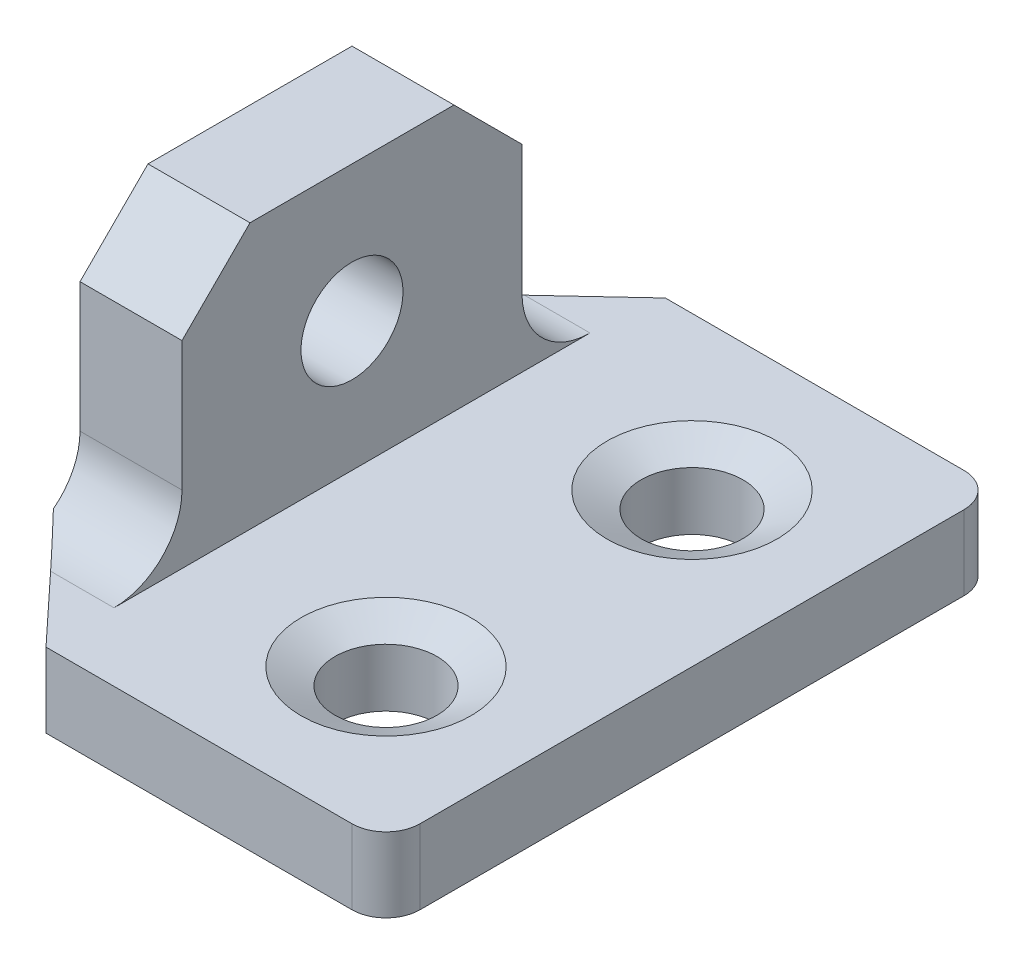
SolidWorks part; units mm, degrees
ref_plane "Front Plane" through (0, 0, 0) normal (0, 0, 1) x (1, 0, 0)
ref_plane "Top Plane" through (0, 0, 0) normal (0, 1, 0) x (1, 0, 0)
ref_plane "Right Plane" through (0, 0, 0) normal (1, 0, 0) x (0, 0, -1)
sketch "Sketch1" plane through (0, 0, 0) normal (0, 1, 0) x (1, 0, 0)
  line L1 (-35, -75) -> (35, -75)
  line L2 (-35, -75) -> (-35, 75)
  line L3 (-35, 75) -> (35, 75)
  line L4 (35, -75) -> (35, 75)
  line L5 (-35, -75) -> (35, 75) construction
  line L6 (-35, 75) -> (35, -75) construction
  point P0 (0, 0)
  dimension "D1" = 150
  dimension "D2" = 70
extrude "Boss-Extrude1" add sketch "Sketch1" along normal blind 5
sketch "Sketch2" plane through (0, 5, 0) normal (0, 1, 0) x (1, 0, 0)
  line L1 (-9, 55) -> (-5, 55)
  line L2 (-9, 55) -> (-9, 70)
  line L3 (-9, 70) -> (-5, 70)
  line L4 (-5, 55) -> (-5, 70)
  line L5 (-9, 55) -> (-5, 70) construction
  line L6 (-9, 70) -> (-5, 55) construction
  line L7 (5, 55) -> (9, 55)
  line L8 (5, 55) -> (5, 70)
  line L9 (5, 70) -> (9, 70)
  line L10 (9, 55) -> (9, 70)
  line L11 (5, 55) -> (9, 70) construction
  line L12 (5, 70) -> (9, 55) construction
  line L13 (0, 0) -> (0, 57.2395) construction
  line L14 (35, 75) -> (-35, 75) construction
  point P0 (-7, 62.5)
  point P5 (7, 62.5)
  dimension "D1" = 15
  dimension "D2" = 15
  dimension "D3" = 4
  dimension "D4" = 4
  dimension "D5" = 10
  dimension "D6" = 5
  dimension "D7" = 5
  dimension "D8" = 5
extrude "Boss-Extrude2" add sketch "Sketch2" along normal blind 15
sketch "Sketch3" plane through (-5, 0, 0) normal (1, 0, 0) x (0, 0, -1)
  line L0 (55, 20) -> (70, 20) construction
  line L1 (55, 20) -> (55, 5) construction
  circle A0 centre (62.5, 12.5) radius 3
  dimension "D1" = 6
  dimension "D2" = 7.5
  dimension "D3" = 7.5
extrude "Boss-Extrude3" add sketch "Sketch3" along normal up to next contours A0
chamfer "Chamfer1" distance 4 angle 45 4 edges at (-7, 20, -55) (7, 20, -55) (7, 20, -70) (-7, 20, -70)
chamfer "Chamfer2" distance 4 angle 45 4 edges at (-7, 5, -70) (7, 5, -70) (7, 5, -55) (-7, 5, -55)
chamfer "Chamfer3" distance 4 angle 45 2 edges at (9, 5, -62.5) (-9, 5, -62.5)
chamfer "Chamfer4" distance 10 angle 45 2 edges at (35, 2.5, -75) (-35, 2.5, -75)
chamfer "Chamfer5" distance 20 angle 45 2 edges at (-35, 2.5, 75) (35, 2.5, 75)
sketch "Sketch4" plane through (0, 5, 0) normal (0, 1, 0) x (1, 0, 0)
  line L0 (0, 0) -> (0, -85.4212) construction
  line L1 (25, -20) -> (25, -30)
  line L2 (25, -30) -> (28, -30)
  line L3 (28, -30) -> (28, -20)
  line L4 (28, -20) -> (25, -20)
  line L5 (-15, -75) -> (15, -75) construction
  line L6 (-25, -30) -> (-28, -30)
  line L7 (-28, -20) -> (-25, -20)
  line L8 (-28, -30) -> (-28, -20)
  line L9 (-25, -20) -> (-25, -30)
  dimension "D1" = 0
  dimension "D2" = 3
  dimension "D3" = 10
  dimension "D4" = 45
  dimension "D5" = 25
extrude "Boss-Extrude4" add sketch "Sketch4" along normal blind 10
chamfer "Chamfer6" distance 2 angle 45 4 edges at (-26.5, 15, 30) (-26.5, 15, 20) (26.5, 15, 20) (26.5, 15, 30)
sketch "Sketch5" plane through (28, 0, 0) normal (1, 0, 0) x (0, 0, -1)
  line L0 (-28, 15) -> (-22, 15) construction
  line L1 (-20, 13) -> (-20, 5) construction
  circle A0 centre (-25, 11) radius 1.5
  dimension "D1" = 3
  dimension "D2" = 4
  dimension "D3" = 5
extrude "Cut-Extrude1" cut sketch "Sketch5" against normal through all
sketch "Sketch6" plane through (35, 0, 0) normal (1, 0, 0) x (0, 0, -1)
  line L1 (-75, 5) -> (44.6022, 5)
  line L2 (-75, 5) -> (-75, -21.1594)
  line L3 (-75, -21.1594) -> (84.3868, -21.1594)
  line L4 (84.3868, 5) -> (84.3868, -21.1594)
  line L5 (44.6022, 35.2539) -> (84.3868, 35.2539)
  line L6 (44.6022, 35.2539) -> (44.6022, 5)
  line L8 (84.3868, 35.2539) -> (84.3868, 5)
extrude "Cut-Extrude2" cut sketch "Sketch6" against normal blind 106
sketch "Sketch7" plane through (28, 0, 0) normal (1, 0, 0) x (0, 0, -1)
  line L0 (-30, 5) -> (-20, 5) construction
  line L1 (-34, 7.1923) -> (-16, 7.1923)
  line L2 (-34, 7.1923) -> (-34, 5)
  line L3 (-34, 5) -> (-16, 5)
  line L4 (-16, 7.1923) -> (-16, 5)
  line L5 (-20, 13) -> (-20, 5) construction
  point P6 (-25, 5)
  point P7 (-25, 7.1923)
  dimension "D1" = 18
  dimension "D2" = 4
extrude "Boss-Extrude5" add sketch "Sketch7" along normal blind 10 and the other way blind 3
chamfer "Chamfer7" distance 3 angle 47 2 edges at (25, 6.0962, 34) (25, 6.0962, 16)
fillet "Fillet1" radius 2 2 edges at (26.5, 7.1923, 30) (26.5, 7.1923, 20)
sketch "Sketch8" plane through (0, 7.1923, 0) normal (0, 1, 0) x (1, 0, 0)
  line L0 (38, -16) -> (38, -34) construction
  line L1 (28.2171, -16) -> (38, -16) construction
  line L2 (28, -34) -> (38, -34) construction
  circle A0 centre (33.5, -20.5) radius 1.5
  circle A1 centre (33.5, -29.5) radius 1.5
  point P4 (33.2644, -29.7436)
  point P5 (32.8471, -20.4875)
  point P6 (33.2644, -20.2966)
  dimension "D1" = 3
  dimension "D2" = 3
  dimension "D3" = 4.5
  dimension "D4" = 4.5
  dimension "D5" = 4.5
  dimension "D6" = 4.5
extrude "Cut-Extrude3" cut sketch "Sketch8" against normal blind 10
chamfer "Chamfer8" distance 1 angle 26 2 edges at (33.5, 7.1923, 22) (33.5, 7.1923, 31)
fillet "Fillet2" radius 1 2 edges at (38, 6.0962, 34) (38, 6.0962, 16)
sketch "Sketch9" plane through (0, 0, 16) normal (0, 0, -1) x (-1, 0, 0)
  line L1 (12.3001, 20.1544) -> (35.9595, 20.1544)
  line L2 (12.3001, 20.1544) -> (12.3001, -1.8639)
  line L3 (12.3001, -1.8639) -> (35.9595, -1.8639)
  line L4 (35.9595, 20.1544) -> (35.9595, -1.8639)
extrude "Cut-Extrude4" cut sketch "Sketch9" against normal blind 20
